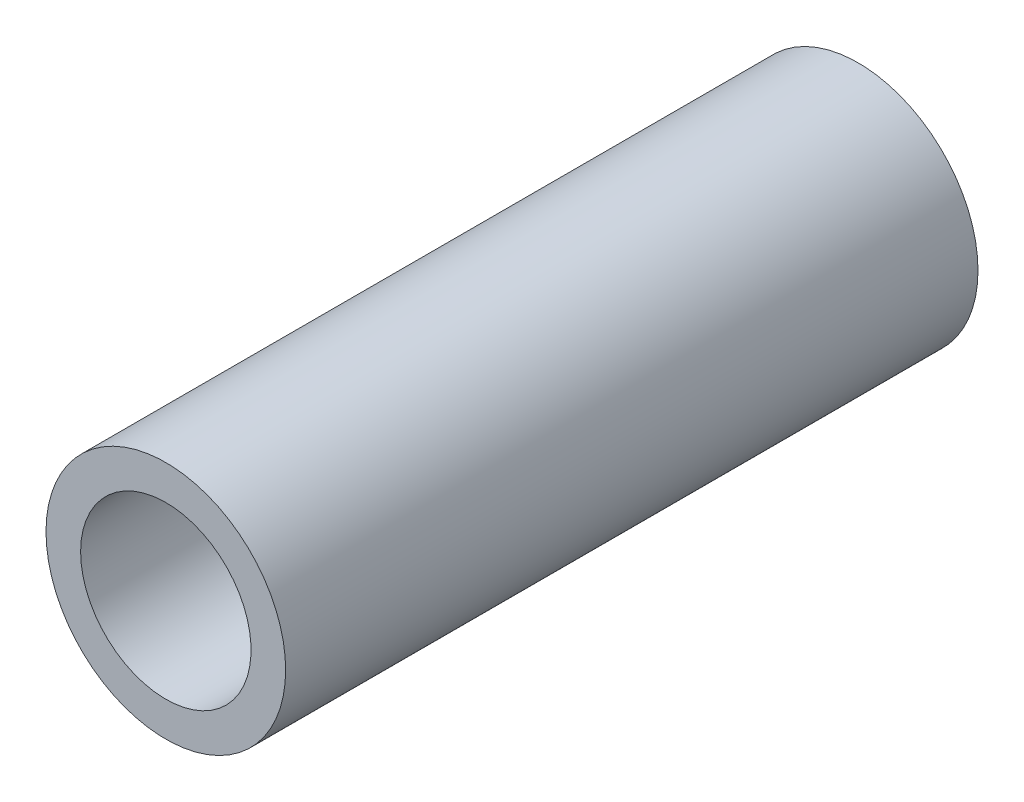
SolidWorks part; units mm, degrees
ref_plane "Front Plane" through (0, 0, 0) normal (0, 0, 1) x (1, 0, 0)
ref_plane "Top Plane" through (0, 0, 0) normal (0, 1, 0) x (1, 0, 0)
ref_plane "Right Plane" through (0, 0, 0) normal (1, 0, 0) x (0, 0, -1)
sketch "Sketch1" plane through (0, 0, 0) normal (0, 0, 1) x (1, 0, 0)
  circle A0 centre (0, 0) radius 2.25
  circle A1 centre (0, 0) radius 1.6
  dimension "OD" = 4.5
  dimension "ID" = 3.2
extrude "Extrude1" add sketch "Sketch1" along normal mid plane 13
sketch "Sketch2" plane through (0, 0, 0) normal (1, 0, 0) x (0, 0, -1)
  line L0 (-6.5, -1.6) -> (6.5, -1.6) construction
  line L3 (6.5, 1.6) -> (-6.5, 1.6) construction
  line L5 (-6.5, -1.6) -> (6.5, -1.6)
  line L6 (6.5, 1.6) -> (-6.5, 1.6)
sketch "Sketch4" plane through (0, 0, 6.5) normal (0, 0, 1) x (1, 0, 0)
  line L0 (0, 0) -> (-1.1314, 1.1314)
  line L1 (0, -2.475) -> (0, 2.475) construction
  circle A0 centre (0, 0) radius 1.6 construction
  dimension "D1" = 45
